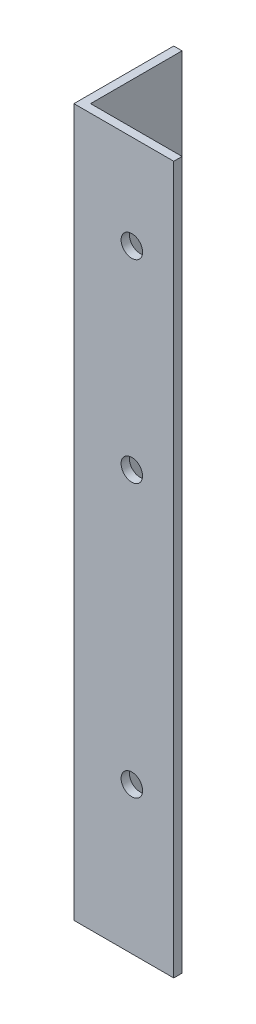
SolidWorks part; units mm, degrees
material "1060 Alloy"
ref_plane "Front Plane" through (0, 0, 0) normal (0, 0, 1) x (1, 0, 0)
ref_plane "Top Plane" through (0, 0, 0) normal (0, 1, 0) x (1, 0, 0)
ref_plane "Right Plane" through (0, 0, 0) normal (1, 0, 0) x (0, 0, -1)
sketch "Sketch1" plane through (0, 0, 0) normal (0, 1, 0) x (1, 0, 0)
  line L0 (0, 0) -> (19.05, 0)
  line L1 (19.05, 0) -> (19.05, 1.5875)
  line L2 (19.05, 1.5875) -> (1.5875, 1.5875)
  line L3 (1.5875, 1.5875) -> (1.5875, 19.05)
  line L4 (1.5875, 19.05) -> (0, 19.05)
  line L5 (0, 19.05) -> (0, 0)
  dimension "D1" = 19.05
  dimension "D2" = 19.05
  dimension "D3" = 1.5875
  dimension "D4" = 1.5875
extrude "Boss-Extrude1" add sketch "Sketch1" along normal blind 135
sketch "Sketch2" plane through (1.5875, 0, 0) normal (1, 0, 0) x (0, 0, -1)
  line L0 (19.05, 135) -> (19.05, 0) construction
  line L1 (1.5875, 135) -> (19.05, 135) construction
  line L2 (19.05, 135) -> (0, 135) construction
  circle A0 centre (11.05, 117) radius 2.05
  circle A1 centre (11.05, 80) radius 2.05
  circle A2 centre (11.05, 28) radius 2.05
  point P12 (10.3187, 135)
  dimension "D1" = 4.1
  dimension "D2" = 8
  dimension "D3" = 18
  dimension "D4" = 55
  dimension "D5" = 107
extrude "Cut-Extrude1" cut sketch "Sketch2" against normal through all
sketch "Sketch3" plane through (0, 0, -1.5875) normal (0, 0, -1) x (-1, 0, 0)
  line L0 (-19.05, 135) -> (-19.05, 0) construction
  line L2 (-19.05, 135) -> (-1.5875, 135) construction
  circle A0 centre (-11.05, 117) radius 2.05
  circle A1 centre (-11.05, 80) radius 2.05
  circle A2 centre (-11.05, 28) radius 2.05
  dimension "D1" = 8
  dimension "D2" = 4.1
  dimension "D5" = 107
  dimension "D3" = 18
  dimension "D4" = 55
extrude "Cut-Extrude2" cut sketch "Sketch3" against normal through all
sketch "Sketch6" plane through (1.5875, 0, 0) normal (1, 0, 0) x (0, 0, -1)
  circle A0 centre (21.95, 105) radius 9.65
  circle A1 centre (21.95, 20) radius 9.65
  circle A2 centre (21.95, 105) radius 9.65 construction
extrude "Cut-Extrude5" cut sketch "Sketch6" against normal blind 10
